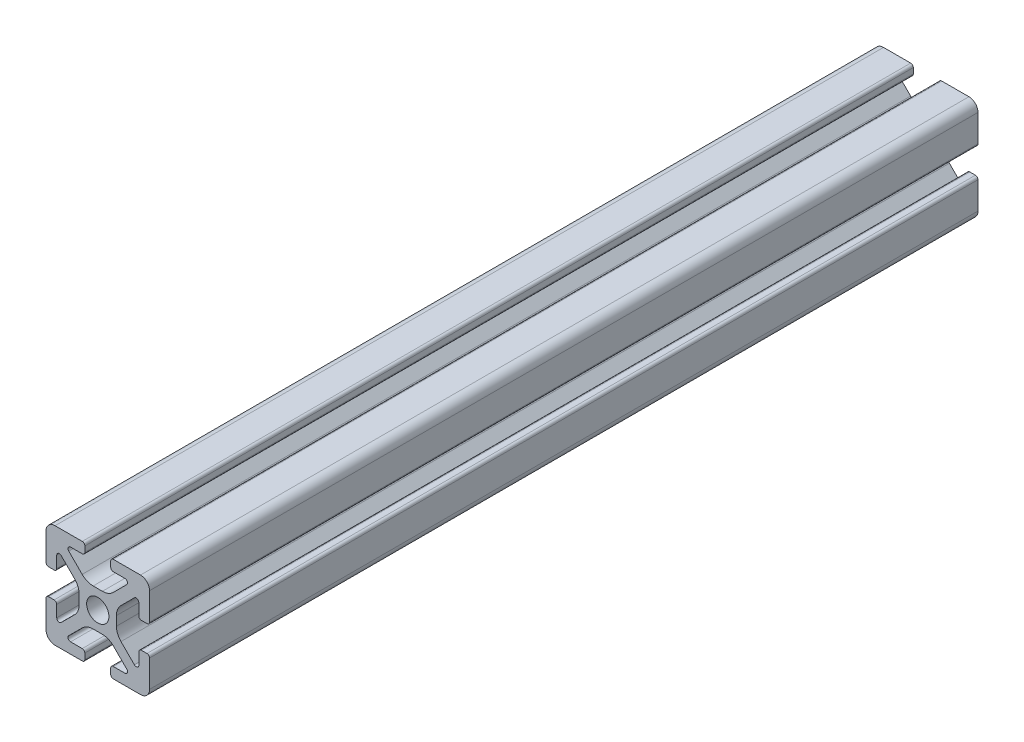
SolidWorks part; units mm, degrees
ref_plane "Front Plane" through (0, 0, 0) normal (0, 0, 1) x (1, 0, 0)
ref_plane "Top Plane" through (0, 0, 0) normal (0, 1, 0) x (1, 0, 0)
ref_plane "Right Plane" through (0, 0, 0) normal (1, 0, 0) x (0, 0, -1)
sketch "Sketch2" plane through (0, 0, 0) normal (0, 0, 1) x (1, 0, 0)
  line L0 (0, 10) -> (0, -10) construction
  line L1 (-10, 0) -> (10, 0) construction
  line L2 (2.5, -10) -> (10, -10)
  line L3 (10, -10) -> (10, -2.5)
  line L4 (2.5, -10) -> (2.5, -7.9246)
  line L5 (2.5, -7.9246) -> (6.4571, -7.9246)
  line L6 (6.4571, -7.9246) -> (2.1325, -3.6)
  line L7 (0, 0) -> (10, -10) construction
  line L8 (10, -2.5) -> (7.9246, -2.5)
  line L9 (7.9246, -2.5) -> (7.9246, -6.4571)
  line L10 (7.9246, -6.4571) -> (3.6, -2.1325)
  line L11 (5.7623, -4.2948) -> (4.2948, -5.7623) construction
  circle A0 centre (0, 0) radius 2.15
  arc A1 (5.25, -7.9246) -> (5.6036, -7.0711) centre (5.25, -7.4246) ccw construction
  point P8 (0, -3.6)
  point P16 (5.0286, -5.0286)
  dimension "Center Hole Diameter" = 4.3
  dimension "D3" = 0.5
  dimension "Rail Height" = 20
  dimension "Rail Width" = 20
  dimension "T-Slot Width" = 5
  dimension "Slot Depth" = 6.4
  dimension "Slot Inner Width" = 11.5
sketch "Sketch3" plane through (0, 0, 0) normal (1, 0, 0) x (0, 0, -1)
  line L0 (-76.2, -10) -> (76.2, -10) construction
  line L1 (-50.8, 0) -> (50.8, 0) construction
  line L2 (0, 10) -> (0, -10) construction
  line L3 (0, 10) -> (0, -10) construction
  point P6 (-50.8, 0)
  point P8 (50.8, 0)
  dimension "D1" = 25.4
  dimension "Length" = 152.4
sketch "Sketch4" plane through (0, 0, 0) normal (0, 0, 1) x (1, 0, 0)
  line L0 (3, -10) -> (8.25, -10)
  line L1 (2.5, -10) -> (10, -10) construction
  line L2 (2.5, -10) -> (2.5, -7.9246) construction
  line L3 (2.5, -7.9246) -> (6.4571, -7.9246) construction
  line L4 (2.5, -8.4246) -> (2.5, -9.5)
  line L5 (3, -7.9246) -> (5.25, -7.9246)
  line L6 (0, -3.6) -> (0.8898, -3.6)
  line L7 (6.4571, -7.9246) -> (2.1325, -3.6) construction
  line L8 (3.0112, -4.4787) -> (5.6036, -7.0711)
  line L9 (10, -10) -> (10, -2.5) construction
  line L10 (7.9246, -6.4571) -> (3.6, -2.1325) construction
  line L11 (7.9246, -2.5) -> (7.9246, -6.4571) construction
  line L12 (7.9246, -5.25) -> (7.9246, -3)
  line L13 (10, -2.5) -> (7.9246, -2.5) construction
  line L14 (8.4246, -2.5) -> (9.5, -2.5)
  line L15 (10, -3) -> (10, -8.25)
  line L16 (7.0711, -5.6036) -> (4.4787, -3.0112)
  line L17 (3.6, 0) -> (3.6, -0.8898)
  line L18 (-10, 0) -> (10, 0) construction
  line L19 (0, -3.6) -> (0, -2.15)
  line L20 (0, 10) -> (0, -10) construction
  line L21 (3.6, 0) -> (2.15, 0)
  arc A0 (2.5, -9.5) -> (3, -10) centre (3, -9.5) ccw
  arc A1 (5.25, -7.9246) -> (5.6036, -7.0711) centre (5.25, -7.4246) ccw construction
  arc A2 (2.5, -8.4246) -> (3, -7.9246) centre (3, -8.4246) cw
  arc A3 (5.25, -7.9246) -> (5.6036, -7.0711) centre (5.25, -7.4246) ccw
  arc A4 (0.8898, -3.6) -> (3.0112, -4.4787) centre (0.8898, -6.6) cw
  arc A5 (8.25, -10) -> (10, -8.25) centre (8.25, -8.25) ccw
  arc A6 (7.0711, -5.6036) -> (7.9246, -5.25) centre (7.4246, -5.25) ccw
  arc A7 (7.9246, -3) -> (8.4246, -2.5) centre (8.4246, -3) cw
  arc A8 (9.5, -2.5) -> (10, -3) centre (9.5, -3) cw
  arc A9 (4.4787, -3.0112) -> (3.6, -0.8898) centre (6.6, -0.8898) cw
  circle A10 centre (0, 0) radius 2.15 construction
  arc A11 (0, -2.15) -> (2.15, 0) centre (0, 0) ccw
  dimension "D1" = 1.75
  dimension "D2" = 3
extrude "Boss-Extrude1" add sketch "Sketch4" along normal mid plane 160
mirror "Mirror1" about plane through (0, 0, 0) normal (1, 0, 0) of bodies 134
mirror "Mirror2" about plane through (0, 0, 0) normal (0, 1, 0) of bodies 135
equation "\"D3@Sketch2\"=\"T-Slot Width@Sketch2\"*0.1"
equation "\"D1@Sketch4\"=\"D3@Sketch2\"*3.5"
equation "\"D2@Sketch4\"=\"D3@Sketch2\"*6"
equation "\"D1@Boss-Extrude1\"=110"
